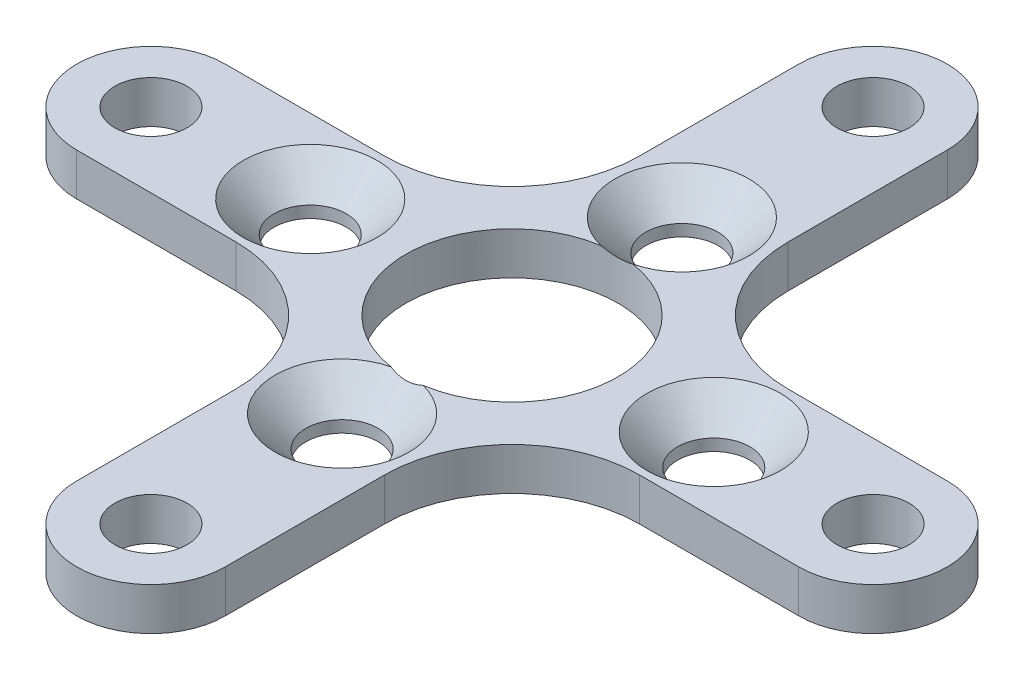
SolidWorks part; units mm, degrees
material "6061-T6 (SS)"
ref_plane "Front Plane" through (0, 0, 0) normal (0, 0, 1) x (1, 0, 0)
ref_plane "Top Plane" through (0, 0, 0) normal (0, 1, 0) x (1, 0, 0)
ref_plane "Right Plane" through (0, 0, 0) normal (1, 0, 0) x (0, 0, -1)
sketch "Sketch1" plane through (0, 0, 0) normal (0, 1, 0) x (1, 0, 0)
  line L0 (3.5, 9.5) -> (3.5, 17)
  line L1 (0, 0) -> (0, 60.2829) construction
  line L2 (0, 0) -> (56.7133, 0) construction
  line L3 (9.5, 3.5) -> (17, 3.5)
  line L4 (-9.5, 3.5) -> (-17, 3.5)
  line L5 (-3.5, 9.5) -> (-3.5, 17)
  line L6 (-3.5, -9.5) -> (-3.5, -17)
  line L7 (-9.5, -3.5) -> (-17, -3.5)
  line L8 (9.5, -3.5) -> (17, -3.5)
  line L9 (3.5, -9.5) -> (3.5, -17)
  circle A0 centre (0, 0) radius 5
  arc A1 (9.5, 3.5) -> (3.5, 9.5) centre (9.5, 9.5) cw
  arc A2 (3.5, 17) -> (-3.5, 17) centre (0, 17) ccw
  arc A3 (17, 3.5) -> (17, -3.5) centre (17, 0) cw
  arc A4 (-17, 3.5) -> (-17, -3.5) centre (-17, 0) ccw
  arc A5 (-9.5, 3.5) -> (-3.5, 9.5) centre (-9.5, 9.5) ccw
  arc A6 (-9.5, -3.5) -> (-3.5, -9.5) centre (-9.5, -9.5) cw
  arc A7 (3.5, -17) -> (-3.5, -17) centre (0, -17) cw
  arc A8 (9.5, -3.5) -> (3.5, -9.5) centre (9.5, -9.5) ccw
  dimension "HoleDiam" = 10
  dimension "Radius" = 6
  dimension "D5" = 3.5
  dimension "D6" = 3.5
  dimension "HalfWidth" = 3.5
  dimension "D3" = 3.5
  dimension "HoleSpacing" = 17
  dimension "D1" = 17
extrude "Boss-Extrude1" add sketch "Sketch1" along normal blind 2
sketch "HoleSpacing" plane through (0, 2, 0) normal (0, 1, 0) x (1, 0, 0)
  line L0 (0, 0) -> (0, 17) construction
  line L2 (17, 0) -> (0, 0) construction
  line L3 (0, 0) -> (0, -17) construction
  line L5 (-17, 0) -> (0, 0) construction
  point P2 (0, 8)
  point P7 (9.5, 0)
  point P8 (-9.5, 0)
  point P9 (0, -8)
  dimension "HoleSpacing" = 34
  dimension "D1" = 34
  dimension "MotorXHole" = 9.5
  dimension "MotorYHole" = 8
  dimension "D4" = 8
  dimension "D5" = 9.5
hole_wizard "M3 Clearance Hole1" positions "Sketch3" profile "Sketch4" hole size "M3" standard "ANSI Metric" end condition through all
sketch "Sketch3" plane through (0, 2, 0) normal (0, 1, 0) x (1, 0, 0)
  point P0 (0, 17)
  point P3 (-17, 0)
  point P6 (17, 0)
  point P9 (0, -17)
sketch "Sketch4" plane through (0, 2, -17) normal (1, 0, 0) x (0, 0, 1)
  line L0 (0, 0) -> (0, 2)
  line L1 (0, 2) -> (1.7, 2)
  line L2 (1.7, 2) -> (1.7, 0)
  line L5 (1.7, 0) -> (0, 0)
  line L11 (0, -6.35) -> (0, 107.95) construction
  dimension "Thru Hole Dia." = 3.4
  dimension "Thru Hole Depth" = 2
hole_wizard "CSK for M3 Flat Head Machine Screw3" positions "Sketch7" profile "Sketch8" countersink size "M3" standard "ANSI Metric" end condition through all
sketch "Sketch7" plane through (0, 2, 0) normal (0, 1, 0) x (1, 0, 0)
  point P0 (0, 8)
  point P3 (-9.5, 0)
  point P6 (0, -8)
  point P9 (9.5, 0)
sketch "Sketch8" plane through (0, 2, -8) normal (1, 0, 0) x (0, 0, 1)
  line L0 (0, 0) -> (0, 2)
  line L1 (0, 2) -> (1.7, 2)
  line L2 (1.7, 2) -> (1.7, 1.45)
  line L3 (1.7, 1.45) -> (3.15, 0)
  line L5 (3.15, 0) -> (0, 0)
  line L6 (-1.7, 1.45) -> (-3.15, 0) construction
  line L11 (0, -6.35) -> (0, 107.95) construction
  dimension "Thru Hole Dia." = 3.4
  dimension "Thru Hole Depth" = 2
  dimension "Near C'Sink Dia." = 6.3
  dimension "Near C'Sink Angle" = 90
equation "\"D5@Sketch1\" = \"HalfWidth@Sketch1\""
equation "\"D6@Sketch1\" = \"HalfWidth@Sketch1\""
equation "\"D3@Sketch1\" = \"HalfWidth@Sketch1\""
equation "\"D1@Sketch1\"=\"HoleSpacing@Sketch1\""
equation "\"D1@HoleSpacing\" = \"HoleSpacing@HoleSpacing\""
equation "\"D5@HoleSpacing\" = \"MotorXHole@HoleSpacing\""
equation "\"D4@HoleSpacing\" = \"MotorYHole@HoleSpacing\""
